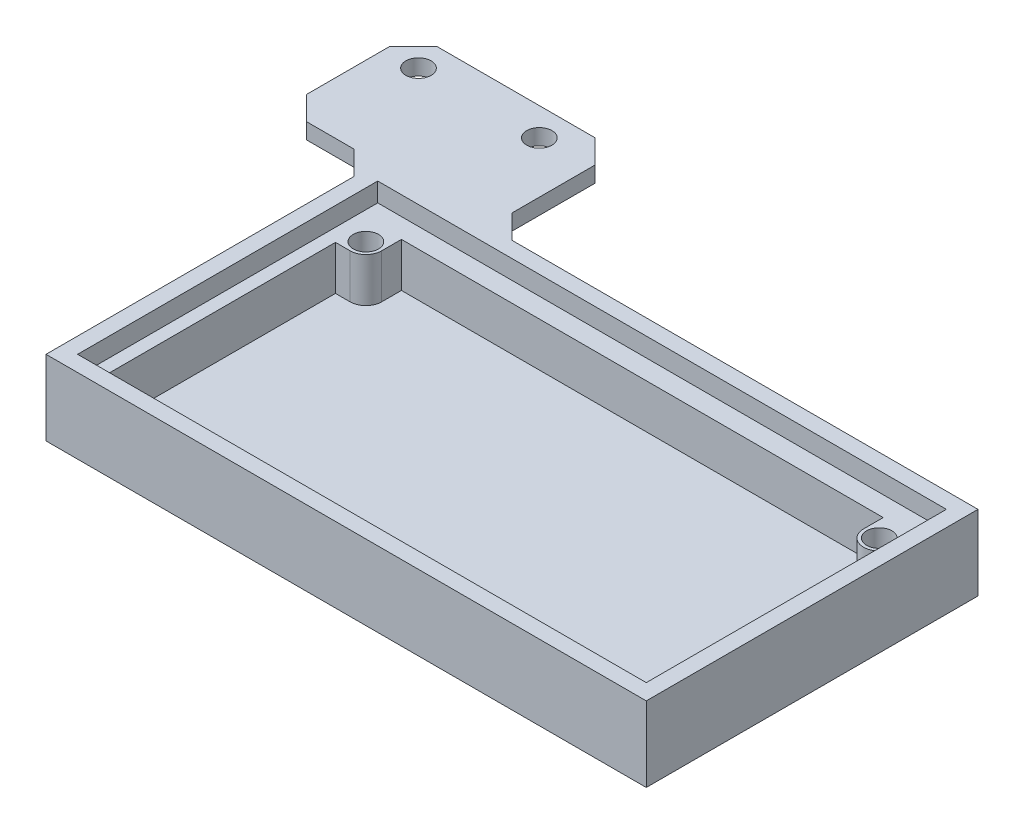
SolidWorks part; units mm, degrees
ref_plane "Front Plane" through (0, 0, 0) normal (0, 0, 1) x (1, 0, 0)
ref_plane "Top Plane" through (0, 0, 0) normal (0, 1, 0) x (1, 0, 0)
ref_plane "Right Plane" through (0, 0, 0) normal (1, 0, 0) x (0, 0, -1)
sketch "Sketch1" plane through (0, 0, 0) normal (0, 1, 0) x (1, 0, 0)
  line L0 (-38, -21) -> (-38, 21)
  line L1 (-36, -19) -> (36, -19)
  line L2 (-36, -19) -> (-36, 19)
  line L3 (-36, 19) -> (36, 19)
  line L4 (36, -19) -> (36, 19)
  line L5 (-36, -19) -> (36, 19) construction
  line L6 (-36, 19) -> (36, -19) construction
  line L7 (-38, 21) -> (38, 21)
  line L8 (38, -21) -> (38, 21)
  line L9 (-38, -21) -> (38, -21)
  point P0 (0, 0)
  dimension "D1" = 72
  dimension "D2" = 38
  dimension "D3" = 2
extrude "Boss-Extrude1" add sketch "Sketch1" along normal blind 8
sketch "Sketch2" plane through (0, 0, 0) normal (0, -1, 0) x (1, 0, 0)
  line L4 (38, 21) -> (-38, 21)
  line L5 (-38, 21) -> (-38, -21)
  line L6 (-38, -21) -> (38, -21)
  line L7 (38, -21) -> (38, 21)
  line L8 (38, 21) -> (-38, 21)
  line L9 (-38, 21) -> (-38, -21)
  line L10 (-38, -21) -> (38, -21)
  line L11 (38, -21) -> (38, 21)
  dimension "D1" = 0
extrude "Boss-Extrude2" add sketch "Sketch2" along normal blind 1.5
sketch "Sketch3" plane through (0, 8, 0) normal (0, 1, 0) x (1, 0, 0)
  line L0 (-36, 19) -> (-36, -19) construction
  line L1 (-36, 16.5) -> (36, 16.5)
  line L2 (-36, 16.5) -> (-36, 19)
  line L3 (-36, 19) -> (36, 19)
  line L4 (-38, -21) -> (38, -21)
  line L5 (38, -21) -> (38, 21)
  line L6 (38, 21) -> (-38, 21)
  line L7 (-38, 21) -> (-38, -21)
  line L8 (-38, -21) -> (38, -21)
  line L9 (38, -21) -> (38, 21)
  line L10 (38, 21) -> (-38, 21)
  line L11 (-38, 21) -> (-38, -21)
  line L12 (36, 16.5) -> (36, 19)
  line L13 (-36, 16.5) -> (36, 19) construction
  line L14 (-36, 19) -> (36, 16.5) construction
  line L15 (-36, -19) -> (36, -19) construction
  line L16 (-36, 16.5) -> (-34.35, 16.5)
  line L17 (-36, 16.5) -> (-36, -19)
  line L18 (-36, -19) -> (-34.35, -19)
  line L19 (-34.35, 16.5) -> (-34.35, -19)
  line L20 (-36, 16.5) -> (-34.35, -19) construction
  line L21 (-36, -19) -> (-34.35, 16.5) construction
  line L22 (32.5, 12) -> (34.35, 12)
  line L23 (36, 16.5) -> (34.35, 16.5)
  line L24 (36, 16.5) -> (36, -19)
  line L25 (36, -19) -> (34.35, -19)
  line L26 (34.35, 16.5) -> (34.35, -19)
  line L27 (36, 16.5) -> (34.35, -19) construction
  line L28 (36, -19) -> (34.35, 16.5) construction
  line L29 (30.5, 14) -> (30.5, 16.5)
  line L30 (-30.5, 14) -> (-30.5, 16.5)
  line L31 (-32.5, 12) -> (-34.35, 12)
  circle A0 centre (32.5, 14) radius 2
  circle A1 centre (-32.5, 14) radius 2
  point P8 (0, 17.75)
  point P15 (-35.175, -1.25)
  point P21 (35.175, -1.25)
  point P37 (0, 0)
  line M23 (-36, 19) -> (36, 19)
  line M24 (36, 19) -> (36, -19)
  line M25 (36, -19) -> (-36, -19)
  line M26 (-36, -19) -> (-36, 19)
  dimension "D5" = 4
  dimension "D6" = 4
  dimension "D2" = 2.5
  dimension "D3" = 1.65
  dimension "D4" = 1.65
  dimension "D1" = 0
extrude "Boss-Extrude3" add sketch "Sketch3" against normal up to surface (7.1 mm away) from offset 2.4 contours L1 M26 M24 M23 | A1 L19 L1 M26 M25 | A1 L30 L1 L19 | A1 L19 L31 | L19 A1 | A1 L19 | A0 L26 | A0 L26 L1 L29 | A0 L26 L1 M25 M24 | L26 A0 offset against normal yes
sketch "Sketch4" plane through (0, 5.6, 0) normal (0, 1, 0) x (1, 0, 0)
  circle A0 centre (32.5, 14) radius 1.6
  circle A1 centre (-32.5, 14) radius 1.6
  dimension "D1" = 3.2
  dimension "D2" = 3.2
extrude "Cut-Extrude1" cut sketch "Sketch4" against normal blind 10
sketch "Sketch6" plane through (0, 0, -21) normal (0, 0, -1) x (-1, 0, 0)
  line L0 (-38, 8) -> (38, 8) construction
  line L1 (24, 6) -> (50, 6)
  line L2 (24, 6) -> (24, 8)
  line L3 (24, 8) -> (50, 8)
  line L4 (50, 6) -> (50, 8)
  line L5 (24, 6) -> (50, 8) construction
  line L6 (24, 8) -> (50, 6) construction
  line L7 (38, 8) -> (38, -1.5) construction
  point P4 (37, 7)
  point P5 (40.7433, 5.78)
  point P8 (36.7552, 7)
  dimension "D1" = 26
  dimension "D2" = 2
  dimension "D3" = 1
extrude "Boss-Extrude4" add sketch "Sketch6" along normal blind 16.5
chamfer "Chamfer1" distance 3 angle 45 1 edges at (-31, 6, -21)
chamfer "Chamfer2" distance 3 angle 45 4 edges at (-24, 5.5, -21) (-24, 7, -37.5) (-50, 7, -37.5) (-50, 7, -21)
sketch "Sketch7" plane through (0, 8, 0) normal (0, 1, 0) x (1, 0, 0)
  circle A0 centre (-30.5, 33.96) radius 1.6
  circle A1 centre (-45.8, 33.96) radius 1.6
  dimension "D1" = 3.2
  dimension "D2" = 3.2
extrude "Cut-Extrude2" cut sketch "Sketch7" against normal through all both and the other way through all
chamfer "Chamfer3" distance 3 angle 45 1 edges at (-38, 7, -21)
